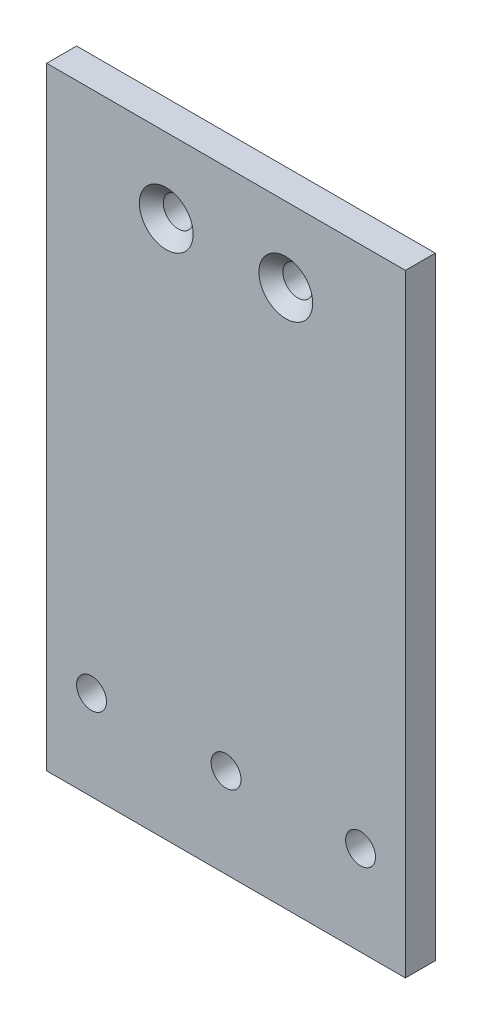
SolidWorks part; units mm, degrees
material "6061-T6 (SS)"
ref_plane "Front Plane" through (0, 0, 0) normal (0, 0, 1) x (1, 0, 0)
ref_plane "Top Plane" through (0, 0, 0) normal (0, 1, 0) x (1, 0, 0)
ref_plane "Right Plane" through (0, 0, 0) normal (1, 0, 0) x (0, 0, -1)
sketch "Sketch1" plane through (0, 0, 0) normal (0, 0, 1) x (1, 0, 0)
  line L1 (-38.1, 69.85) -> (38.1, 69.85)
  line L2 (-38.1, 69.85) -> (-38.1, -69.85)
  line L3 (-38.1, -69.85) -> (38.1, -69.85)
  line L4 (38.1, 69.85) -> (38.1, -69.85)
  line L5 (-38.1, 69.85) -> (38.1, -69.85) construction
  line L6 (-38.1, -69.85) -> (38.1, 69.85) construction
  point P0 (0, 0)
  dimension "D1" = 139.7
  dimension "D2" = 76.2
extrude "Boss-Extrude1" add sketch "Sketch1" along normal blind 6.35
sketch "Sketch2" plane through (0, 0, 6.35) normal (0, 0, 1) x (1, 0, 0)
  line L0 (38.1, 69.85) -> (-38.1, 69.85) construction
  line L1 (-38.1, 69.85) -> (-38.1, -69.85) construction
  line L2 (38.1, -69.85) -> (38.1, 69.85) construction
  line L3 (-38.1, -69.85) -> (38.1, -69.85) construction
  circle A0 centre (-12.7, 44.45) radius 3.175
  circle A1 centre (12.7, 44.45) radius 3.175
  circle A2 centre (-28.575, -50.8) radius 3.175
  circle A3 centre (0, -50.8) radius 3.175
  circle A4 centre (28.575, -50.8) radius 3.175
  dimension "D5" = 6.35
  dimension "D6" = 6.35
  dimension "D7" = 6.35
  dimension "D8" = 6.35
  dimension "D9" = 6.35
  dimension "D1" = 25.4
  dimension "D2" = 25.4
  dimension "D3" = 25.4
  dimension "D4" = 25.4
  dimension "D10" = 19.05
  dimension "D11" = 19.05
  dimension "D12" = 19.05
  dimension "D13" = 9.525
  dimension "D14" = 9.525
  dimension "D15" = 38.1
extrude "Cut-Extrude1" cut sketch "Sketch2" against normal blind 6.35
chamfer "Chamfer2" distance 2.54 angle 45 2 edges at (15.875, 44.45, 6.35) (-9.525, 44.45, 6.35)
sketch "Sketch3" plane through (-38.1, 0, 0) normal (-1, 0, 0) x (0, 0, 1)
  line L0 (6.35, 69.85) -> (6.35, -69.85) construction
  line L1 (0, 69.85) -> (6.35, 69.85)
  line L2 (0, 69.85) -> (0, 60.325)
  line L3 (0, 60.325) -> (6.35, 60.325)
  line L4 (6.35, 69.85) -> (6.35, 60.325)
  dimension "D1" = 9.525
extrude "Cut-Extrude2" cut sketch "Sketch3" against normal through all
